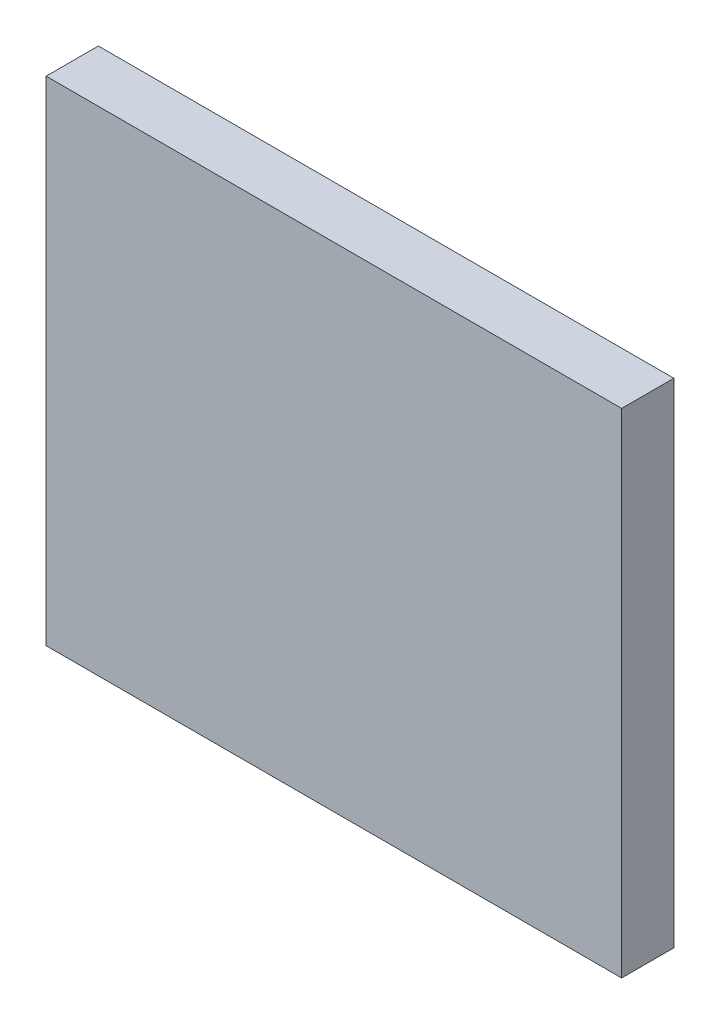
SolidWorks part; units mm, degrees
ref_plane "Front Plane" through (0, 0, 0) normal (0, 0, 1) x (1, 0, 0)
ref_plane "Top Plane" through (0, 0, 0) normal (0, 1, 0) x (1, 0, 0)
ref_plane "Right Plane" through (0, 0, 0) normal (1, 0, 0) x (0, 0, -1)
sketch "Sketch1" plane through (0, 0, 0) normal (0, 0, 1) x (1, 0, 0)
  line L1 (140, -120) -> (-140, -120)
  line L2 (140, -120) -> (140, 120)
  line L3 (140, 120) -> (-140, 120)
  line L4 (-140, -120) -> (-140, 120)
  line L5 (140, -120) -> (-140, 120) construction
  line L6 (140, 120) -> (-140, -120) construction
  point P0 (0, 0)
  dimension "D1" = 280
  dimension "D2" = 240
extrude "Boss-Extrude1" add sketch "Sketch1" along normal blind 25.4
